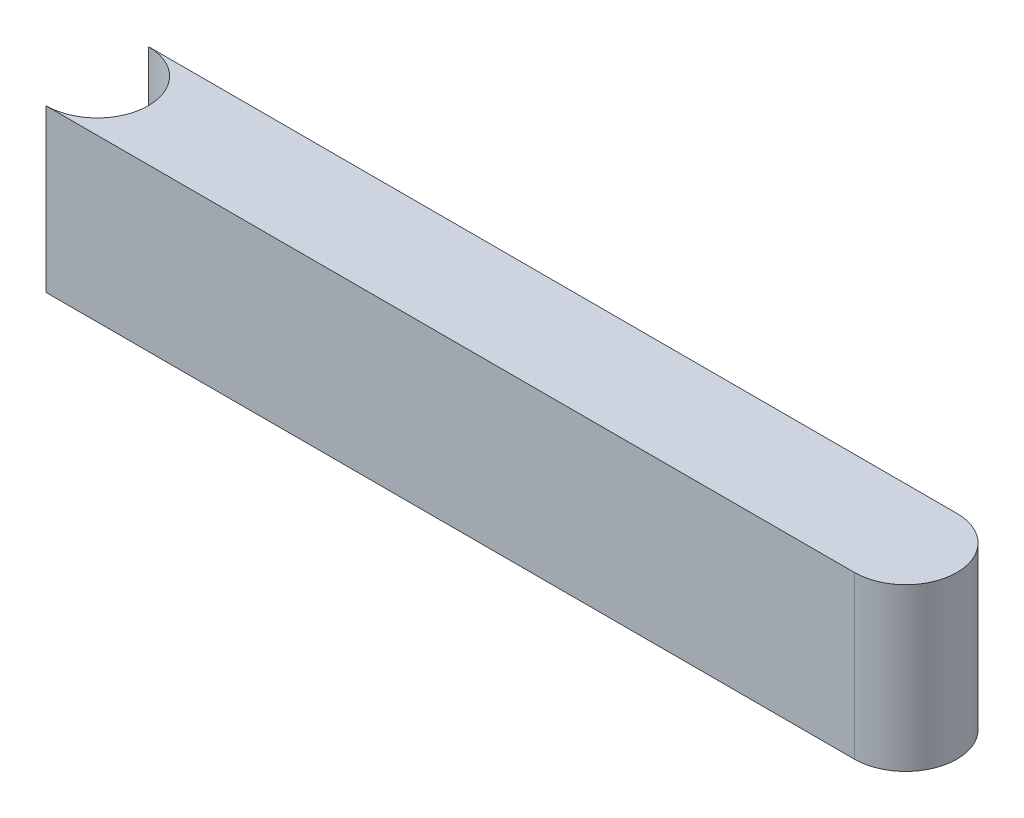
SolidWorks part; units mm, degrees
ref_plane "Front Plane" through (0, 0, 0) normal (0, 0, 1) x (1, 0, 0)
ref_plane "Top Plane" through (0, 0, 0) normal (0, 1, 0) x (1, 0, 0)
ref_plane "Right Plane" through (0, 0, 0) normal (1, 0, 0) x (0, 0, -1)
sketch "Sketch1" plane through (0, 0, 0) normal (0, 1, 0) x (1, 0, 0)
  line L0 (0, 0) -> (150, 0)
  line L1 (150, -19) -> (0, -19)
  arc A0 (150, 0) -> (150, -19) centre (150, -9.5) cw
  arc A1 (0, -19) -> (0, 0) centre (0, -9.5) ccw
  dimension "D1" = 9.5
  dimension "D2" = 150
extrude "Boss-Extrude1" add sketch "Sketch1" along normal blind 30
